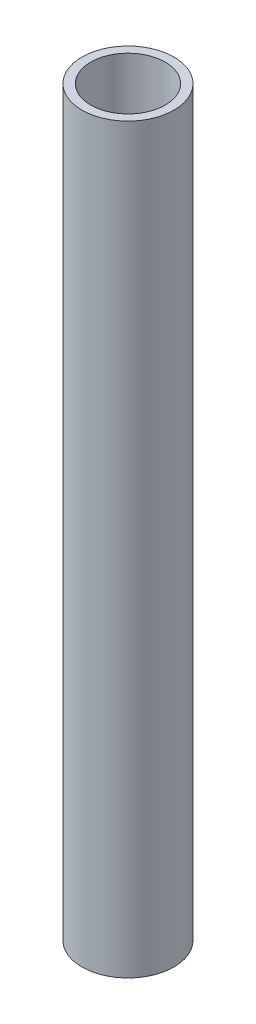
SolidWorks part; units mm, degrees
ref_plane "Front Plane" through (0, 0, 0) normal (0, 0, 1) x (1, 0, 0)
ref_plane "Top Plane" through (0, 0, 0) normal (0, 1, 0) x (1, 0, 0)
ref_plane "Right Plane" through (0, 0, 0) normal (1, 0, 0) x (0, 0, -1)
sketch "Sketch1" plane through (0, 0, 0) normal (0, 1, 0) x (1, 0, 0)
  circle A0 centre (0, 0) radius 5.25
  dimension "D1" = 10.5
extrude "Boss-Extrude1" add sketch "Sketch1" along normal blind 84.6582
sketch "Sketch3" plane through (0, 84.6582, 0) normal (0, 1, 0) x (1, 0, 0)
  circle A0 centre (0, 0) radius 4.25
  point P3 (-9.1213, 0)
  dimension "D1" = 8.5
extrude "Cut-Extrude1" cut sketch "Sketch3" against normal blind 30
